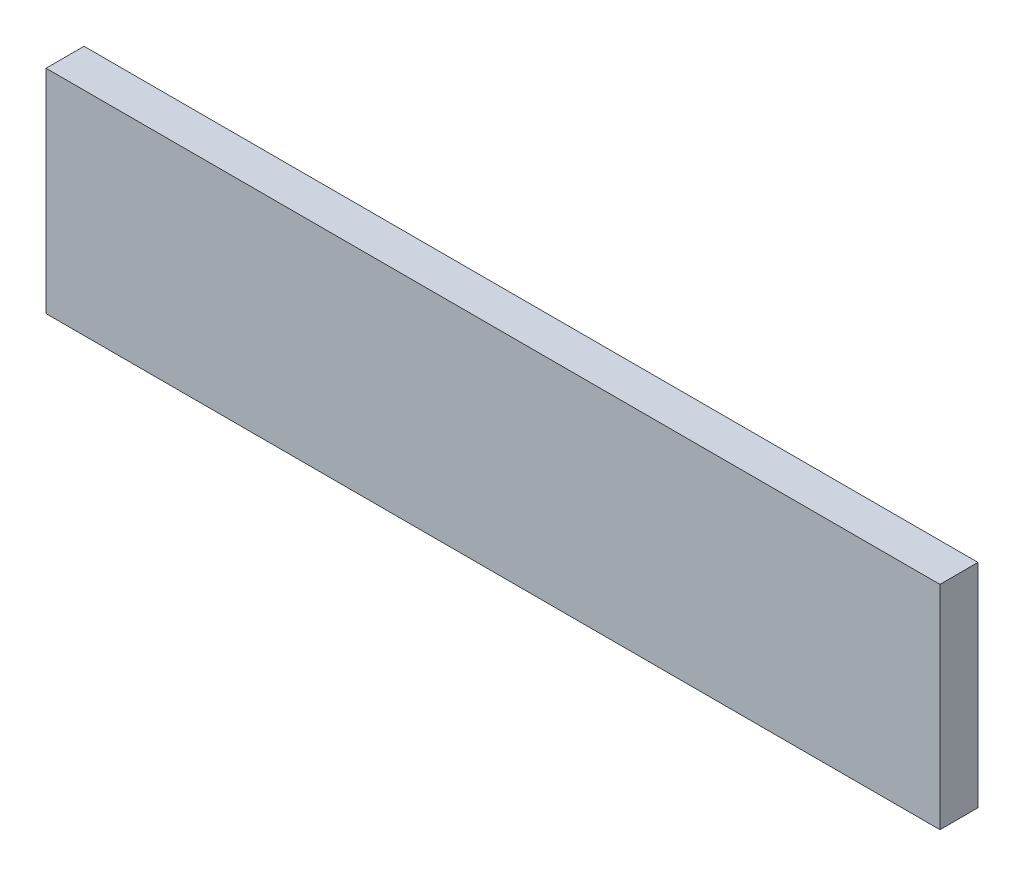
SolidWorks part; units mm, degrees
ref_plane "Front Plane" through (0, 0, 0) normal (0, 0, 1) x (1, 0, 0)
ref_plane "Top Plane" through (0, 0, 0) normal (0, 1, 0) x (1, 0, 0)
ref_plane "Right Plane" through (0, 0, 0) normal (1, 0, 0) x (0, 0, -1)
other "Configuration Table"
sketch "Sketch1" plane through (0, 0, 0) normal (0, 0, 1) x (1, 0, 0)
  line L1 (-117.4904, -27.9262) -> (117.4904, -27.9262)
  line L2 (-117.4904, -27.9262) -> (-117.4904, 27.9262)
  line L3 (-117.4904, 27.9262) -> (117.4904, 27.9262)
  line L4 (117.4904, -27.9262) -> (117.4904, 27.9262)
  line L5 (-117.4904, -27.9262) -> (117.4904, 27.9262) construction
  line L6 (-117.4904, 27.9262) -> (117.4904, -27.9262) construction
  point P0 (0, 0)
extrude "Boss-Extrude1" add sketch "Sketch1" along normal blind 10
